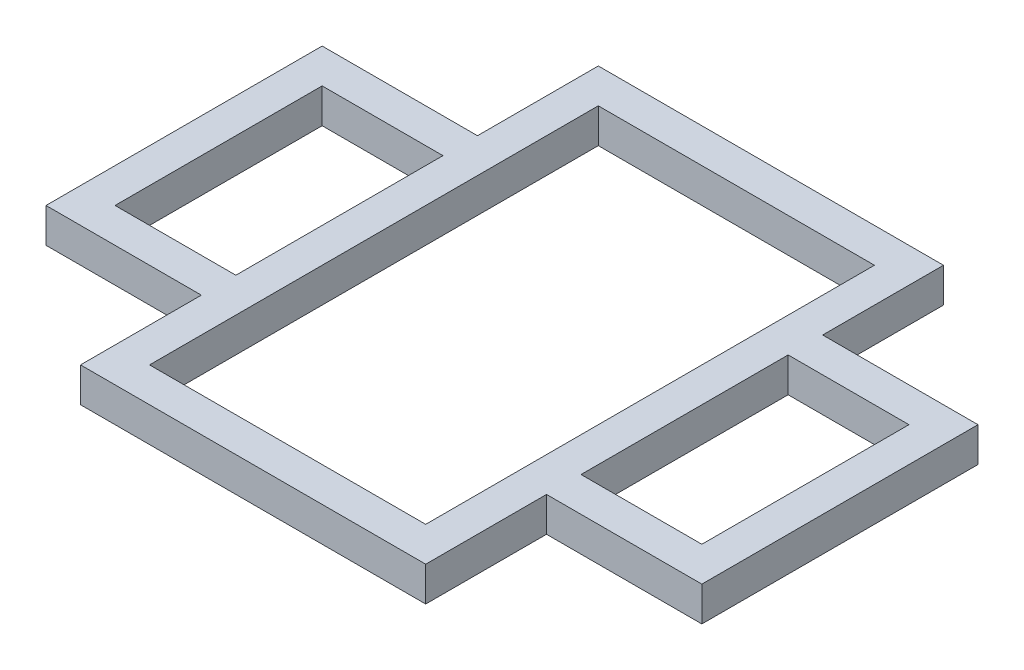
SolidWorks part; units mm, degrees
ref_plane "Front Plane" through (0, 0, 0) normal (0, 0, 1) x (1, 0, 0)
ref_plane "Top Plane" through (0, 0, 0) normal (0, 1, 0) x (1, 0, 0)
ref_plane "Right Plane" through (0, 0, 0) normal (1, 0, 0) x (0, 0, -1)
sketch "Sketch4" plane through (0, 0, 0) normal (0, 1, 0) x (1, 0, 0)
  line L0 (-100, 150) -> (100, 150)
  line L1 (170, -60) -> (100, -60)
  line L2 (100, -150) -> (-100, -150)
  line L3 (190, -80) -> (100, -80)
  line L4 (-80, 130) -> (-10, 130)
  line L5 (-80, -40) -> (-80, -60)
  line L6 (-80, 40) -> (-80, 60)
  line L7 (-80, 60) -> (-80, 130)
  line L8 (10, 130) -> (80, 130)
  line L9 (80, 130) -> (80, 60)
  line L10 (-10, 130) -> (10, 130)
  line L11 (80, 60) -> (80, 40)
  line L12 (80, -40) -> (80, -60)
  line L13 (10, -130) -> (-10, -130)
  line L15 (-80, -40) -> (-80, 40)
  line L17 (80, 40) -> (80, -40)
  line L22 (-10, -130) -> (-80, -130)
  line L23 (-80, -130) -> (-80, -60)
  line L25 (80, -60) -> (80, -130)
  line L26 (80, -130) -> (10, -130)
  line L28 (170, 60) -> (100, 60)
  line L29 (170, 60) -> (170, -60)
  line L30 (190, 80) -> (100, 80)
  line L31 (-100, 80) -> (-190, 80)
  line L32 (-170, 60) -> (-170, -60)
  line L33 (-100, 60) -> (-170, 60)
  line L34 (-100, -60) -> (-170, -60)
  line L35 (190, 80) -> (190, -80)
  line L36 (-100, -80) -> (-190, -80)
  line L37 (-190, 80) -> (-190, -80)
  line L44 (-100, 150) -> (-100, 80)
  line L45 (-100, 60) -> (-100, -60)
  line L46 (-100, -80) -> (-100, -150)
  line L47 (100, -150) -> (100, -80)
  line L48 (100, -60) -> (100, 60)
  line L49 (100, 80) -> (100, 150)
  point P13 (-45, 130)
  point P25 (-80, -95)
  dimension "D1" = 300
  dimension "D3" = 150
  dimension "D4" = 70
  dimension "D5" = 20
  dimension "D6" = 70
  dimension "D7" = 20
  dimension "D8" = 20
  dimension "D16" = 20
  dimension "D32" = 20
  dimension "D36" = 20
extrude "Boss-Extrude2" add sketch "Sketch4" along normal blind 20
